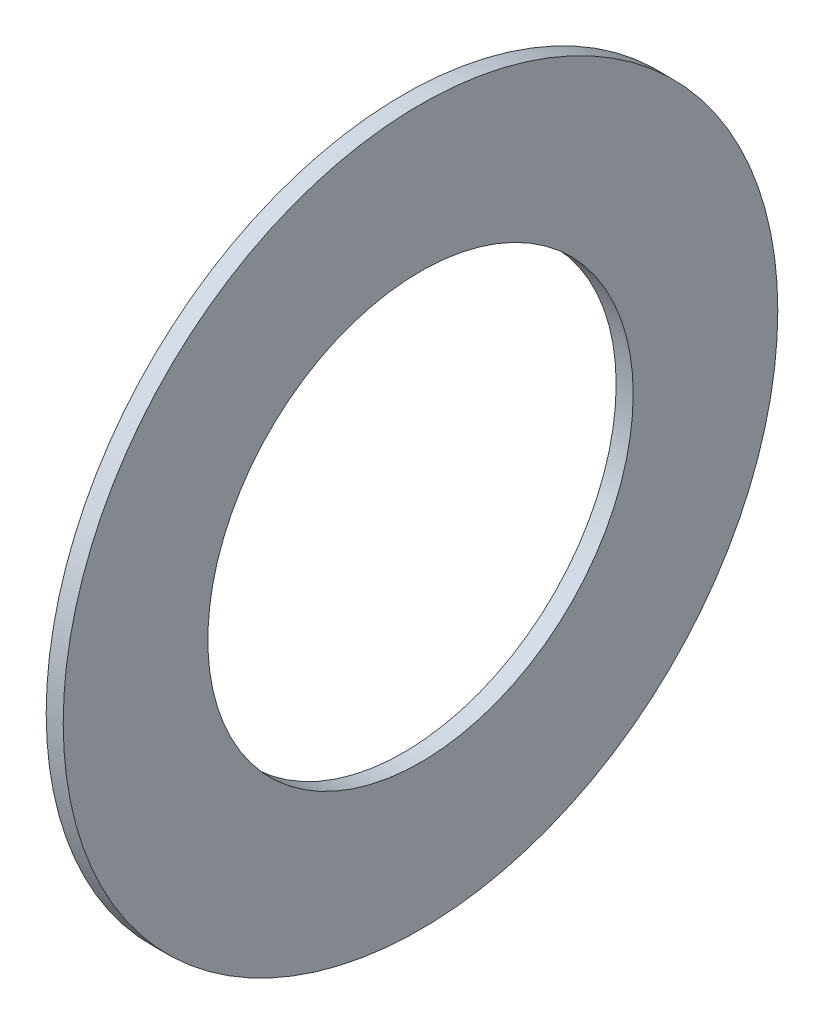
SolidWorks part; units mm, degrees
ref_plane "Front Plane" through (0, 0, 0) normal (0, 0, 1) x (1, 0, 0)
ref_plane "Top Plane" through (0, 0, 0) normal (0, 1, 0) x (1, 0, 0)
ref_plane "Right Plane" through (0, 0, 0) normal (1, 0, 0) x (0, 0, -1)
sketch "Sketch1" plane through (0, 0, 0) normal (1, 0, 0) x (0, 0, -1)
  circle A0 centre (0, 0) radius 21
  circle A1 centre (0, 0) radius 12.5
  dimension "OD" = 42
  dimension "Shaft Dia" = 25
extrude "Extrude1" add sketch "Sketch1" along normal blind 1
